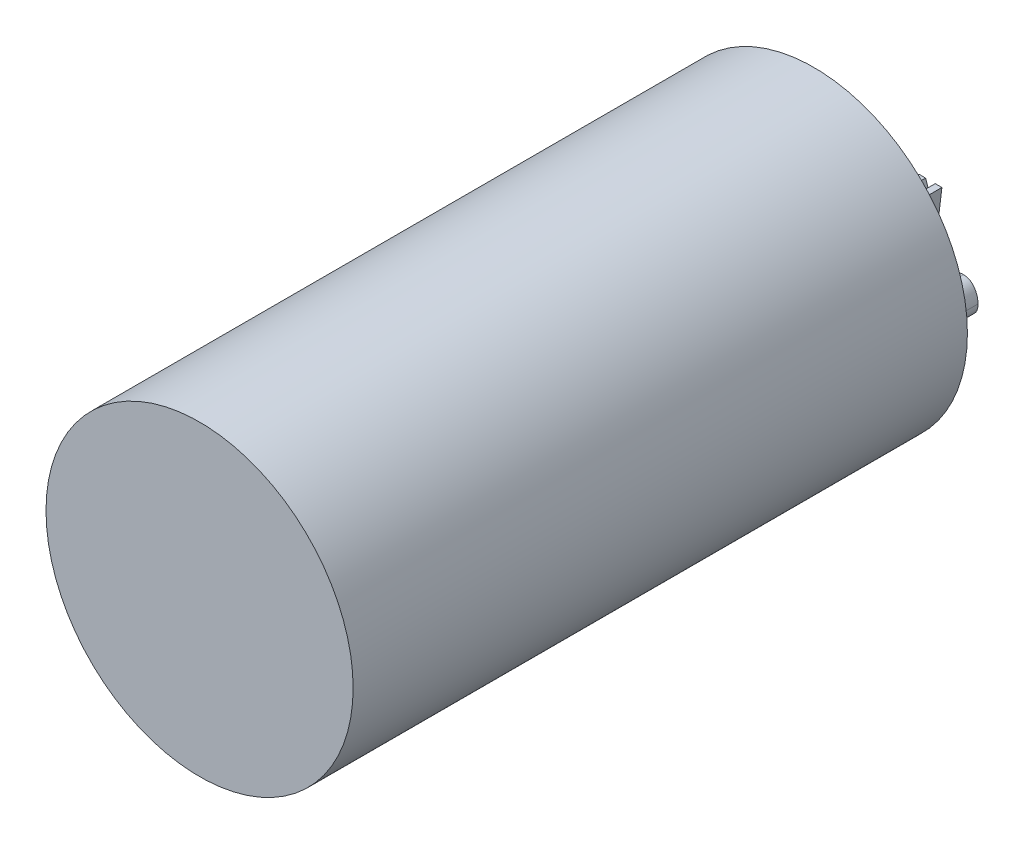
SolidWorks part; units mm, degrees
ref_plane "Front Plane" through (0, 0, 0) normal (0, 0, 1) x (1, 0, 0)
ref_plane "Top Plane" through (0, 0, 0) normal (0, 1, 0) x (1, 0, 0)
ref_plane "Right Plane" through (0, 0, 0) normal (1, 0, 0) x (0, 0, -1)
sketch "Sketch1" plane through (0, 0, 0) normal (0, 0, 1) x (1, 0, 0)
  circle A0 centre (0, 0) radius 15
extrude "Boss-Extrude1" add sketch "Sketch1" along normal blind 60
sketch "Sketch2" plane through (0, 0, 0) normal (0, 0, -1) x (-1, 0, 0)
  text T0 "   WHEEL \r\nCLAP ROD" font "Franklin Gothic Medium" height in points 12
extrude "Boss-Extrude2" add sketch "Sketch2" along normal blind 5
